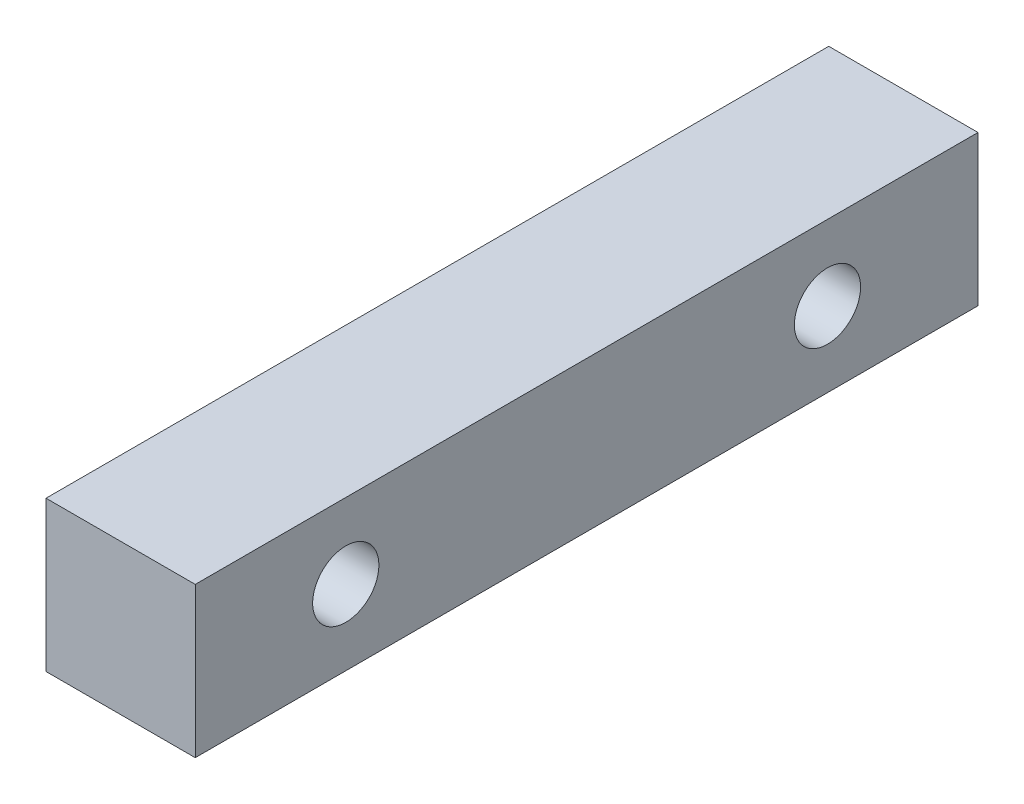
SolidWorks part; units mm, degrees
ref_plane "Front Plane" through (0, 0, 0) normal (0, 0, 1) x (1, 0, 0)
ref_plane "Top Plane" through (0, 0, 0) normal (0, 1, 0) x (1, 0, 0)
ref_plane "Right Plane" through (0, 0, 0) normal (1, 0, 0) x (0, 0, -1)
sketch "Sketch1" plane through (0, 0, 0) normal (0, 0, 1) x (1, 0, 0)
  line L1 (-42.4, 120.65) -> (-30.0057, 120.65)
  line L2 (-42.4, 120.65) -> (-42.4, 108.1854)
  line L3 (-42.4, 108.1854) -> (-30.0057, 108.1854)
  line L4 (-30.0057, 120.65) -> (-30.0057, 108.1854)
  point P5 (0, 0)
extrude "Boss-Extrude1" add sketch "Sketch1" against normal up to surface (65 mm away)
sketch "Sketch2" plane through (-42.4, 0, 0) normal (-1, 0, 0) x (0, 0, 1)
  line L0 (-65, 114.4177) -> (0, 114.4177) construction
  line L1 (-65, 120.65) -> (-65, 108.1854) construction
  line L2 (0, 120.65) -> (0, 108.1854) construction
  line L3 (-32.5, 120.65) -> (-32.5, 108.1854) construction
  line L4 (-65, 120.65) -> (0, 120.65) construction
  line L5 (-65, 108.1854) -> (0, 108.1854) construction
  circle A0 centre (-52.5, 114.4177) radius 2.75
  circle A1 centre (-12.5, 114.4177) radius 2.75
  dimension "D1" = 5.5
  dimension "D2" = 20
extrude "Cut-Extrude1" cut sketch "Sketch2" along normal up to surface and the other way up to surface
